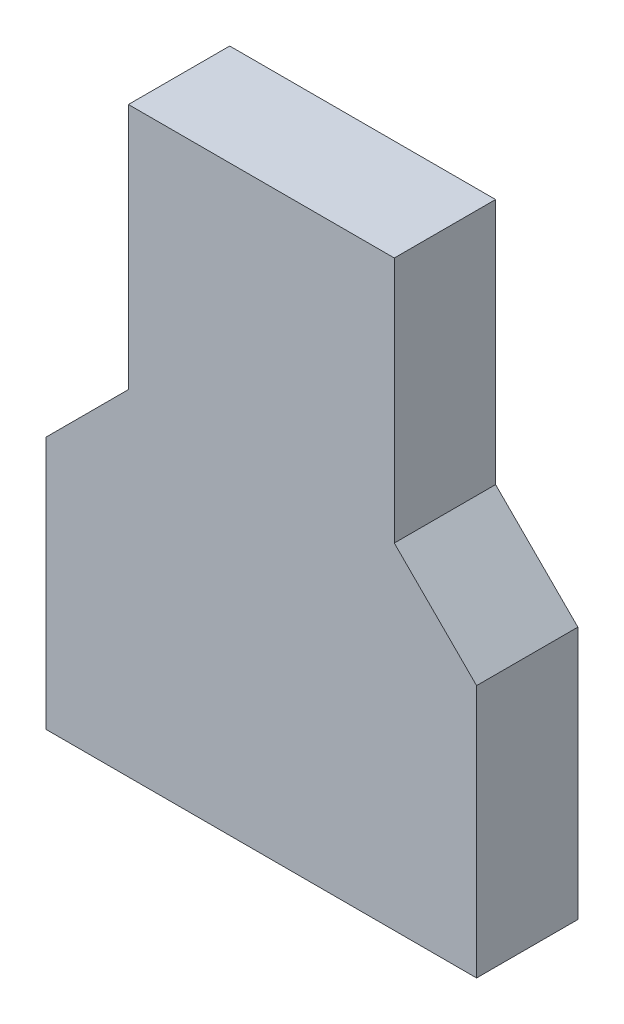
SolidWorks part; units mm, degrees
ref_plane "Front Plane" through (0, 0, 0) normal (0, 0, 1) x (1, 0, 0)
ref_plane "Top Plane" through (0, 0, 0) normal (0, 1, 0) x (1, 0, 0)
ref_plane "Right Plane" through (0, 0, 0) normal (1, 0, 0) x (0, 0, -1)
sketch "Sketch1" plane through (0, 0, 0) normal (0, 0, 1) x (1, 0, 0)
  line L0 (2.625, -5.75) -> (4.25, -5.75)
  line L1 (-2.625, -5.75) -> (2.625, -5.75)
  line L2 (-2.625, 0.875) -> (-2.625, 5.75)
  line L3 (-2.625, 5.75) -> (2.625, 5.75)
  line L4 (2.625, 0.875) -> (2.625, 5.75)
  line L5 (-2.625, -5.75) -> (2.625, 5.75) construction
  line L6 (-2.625, 5.75) -> (2.625, -5.75) construction
  line L7 (4.25, -5.75) -> (4.25, -0.75)
  line L8 (4.25, -0.75) -> (2.625, 0.875)
  line L9 (0, 0) -> (0, -5.75) construction
  line L10 (-2.625, -5.75) -> (-4.25, -5.75)
  line L11 (-4.25, -5.75) -> (-4.25, -0.75)
  line L12 (-4.25, -0.75) -> (-2.625, 0.875)
  point P0 (0, 0)
  dimension "D1" = 5.25
  dimension "D2" = 11.5
  dimension "D3" = 5
  dimension "D4" = 4.25
  dimension "D5" = 45
extrude "Boss-Extrude1" add sketch "Sketch1" along normal mid plane 2
